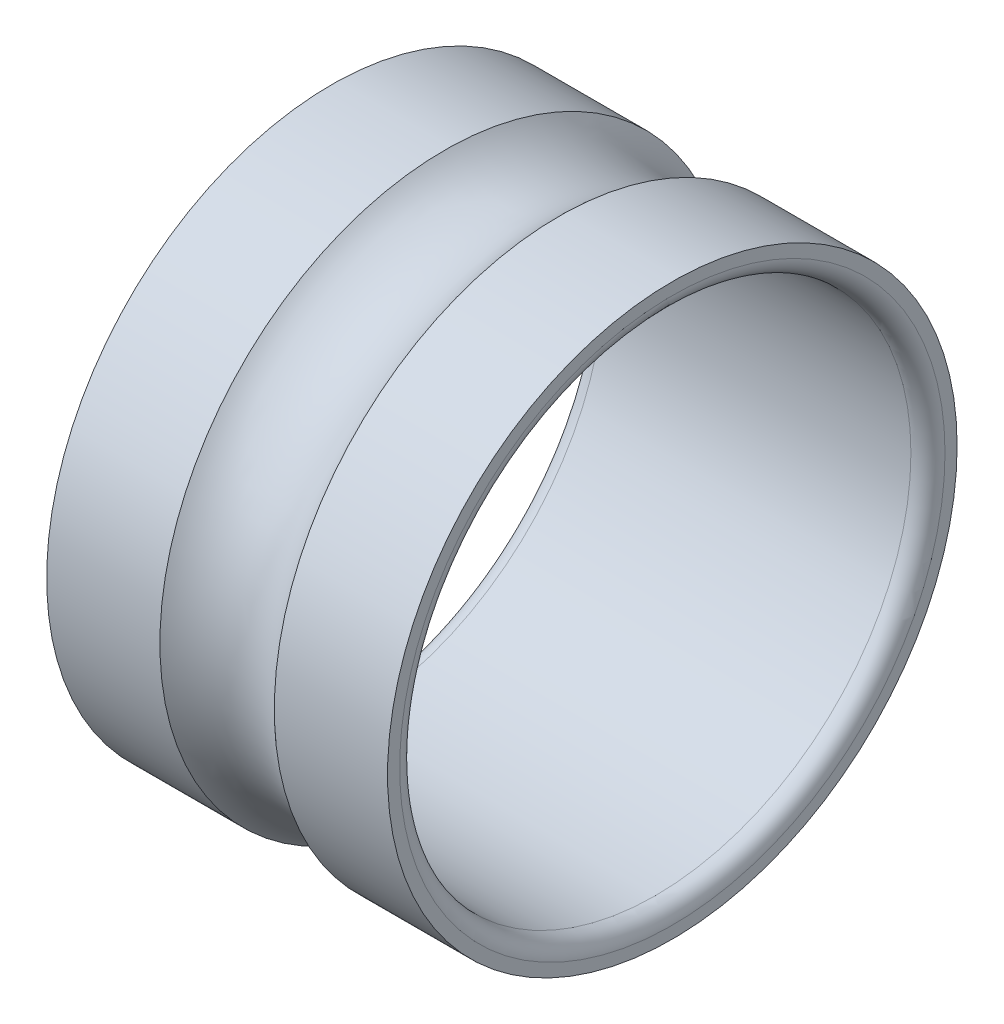
SolidWorks part; units mm, degrees
material "AISI 347 Annealed Stainless Steel (SS)"
ref_plane "Front Plane" through (0, 0, 0) normal (0, 0, 1) x (1, 0, 0)
ref_plane "Top Plane" through (0, 0, 0) normal (0, 1, 0) x (1, 0, 0)
ref_plane "Right Plane" through (0, 0, 0) normal (1, 0, 0) x (0, 0, -1)
sketch "Sketch1" plane through (0, 0, 0) normal (0, 0, 1) x (1, 0, 0)
  line L0 (-1.4287, 2.3813) -> (1.4287, 2.3813)
  line L1 (1.5875, 2.54) -> (1.5875, 2.6527)
  line L2 (1.5875, 2.6527) -> (0.5328, 2.6527)
  line L3 (-0.5328, 2.6527) -> (-1.5875, 2.6527)
  line L4 (-1.5875, 2.6527) -> (-1.5875, 2.54)
  line L5 (-1.5875, 0) -> (1.5875, 0) construction
  arc A0 (-1.5875, 2.54) -> (-1.4287, 2.3813) centre (-1.4287, 2.54) ccw
  arc A1 (1.4287, 2.3813) -> (1.5875, 2.54) centre (1.4287, 2.54) ccw
  arc A2 (0.5328, 2.6527) -> (-0.5328, 2.6527) centre (0, 3.175) cw
revolve "Revolve1" add sketch "Sketch1" angle 360 about L5
